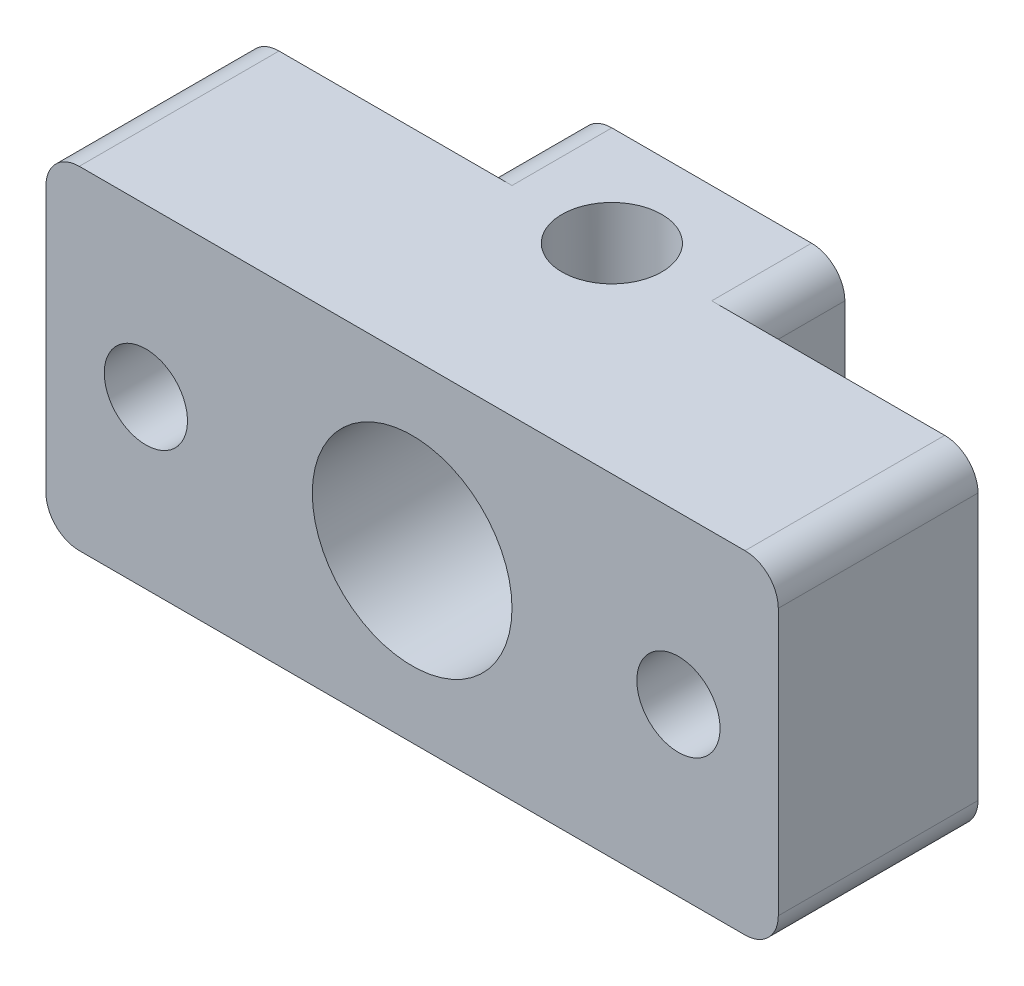
SolidWorks part; units mm, degrees
material "6061 合金"
ref_plane "前视基准面" through (0, 0, 0) normal (0, 0, 1) x (1, 0, 0)
ref_plane "上视基准面" through (0, 0, 0) normal (0, 1, 0) x (1, 0, 0)
ref_plane "右视基准面" through (0, 0, 0) normal (1, 0, 0) x (0, 0, -1)
sketch "草图1" plane through (0, 0, 0) normal (0, 0, 1) x (1, 0, 0)
  line L1 (-11, -5) -> (11, -5)
  line L2 (-11, -5) -> (-11, 5)
  line L3 (-11, 5) -> (11, 5)
  line L4 (11, -5) -> (11, 5)
  line L5 (0, 5) -> (0, -5) construction
  line L6 (-11, 0) -> (11, 0) construction
  circle A0 centre (8, 0) radius 1.25
  circle A1 centre (-8, 0) radius 1.25
  circle A2 centre (0, 0) radius 3
  point P0 (0, 0)
  dimension "D1" = 8
  dimension "D4" = 6
  dimension "D5" = 2.5
  dimension "D2" = 22
  dimension "D3" = 10
extrude "凸台-拉伸1" add sketch "草图1" along normal blind 9
cosmetic thread "装饰螺纹线1" parameters "D2"=3
cosmetic thread "装饰螺纹线2" parameters "D2"=3
sketch "草图2" plane through (0, -5, 0) normal (0, -1, 0) x (1, 0, 0)
  line L0 (-11, 9) -> (11, 9) construction
  circle A0 centre (0, 3) radius 1.5
  dimension "D1" = 6
  dimension "D2" = 3
extrude "切除-拉伸1" cut sketch "草图2" against normal blind 11
cosmetic thread "装饰螺纹线3" parameters "D2"=4
sketch "草图4" plane through (0, -5, 0) normal (0, -1, 0) x (1, 0, 0)
  line L0 (-11, 9) -> (-11, 0) construction
  line L1 (-11, 3) -> (-4, 3)
  line L2 (-11, 3) -> (-11, 0)
  line L3 (-11, 0) -> (-4, 0)
  line L4 (-4, 3) -> (-4, 0)
  line L5 (-11, 3) -> (-4, 0) construction
  line L6 (-11, 0) -> (-4, 3) construction
  line L7 (-11, 0) -> (11, 0) construction
  line L8 (0, 9.6149) -> (0, -2.6706) construction
  line L9 (11, 0) -> (4, 3) construction
  line L10 (11, 3) -> (4, 0) construction
  line L11 (4, 3) -> (4, 0)
  line L12 (11, 0) -> (4, 0)
  line L13 (11, 3) -> (11, 0)
  line L14 (11, 3) -> (4, 3)
  point P4 (-7.5, 1.5)
  point P16 (7.5, 1.5)
  dimension "D1" = 7
  dimension "D2" = 3
extrude "切除-拉伸2" cut sketch "草图4" against normal blind 10
fillet "圆角1" radius 1 8 edges at (11, -5, 6) (-11, 5, 6) (11, 5, 6) (-11, -5, 6) (4, 5, 1.5) (-4, -5, 1.5) (4, -5, 1.5) (-4, 5, 1.5)
